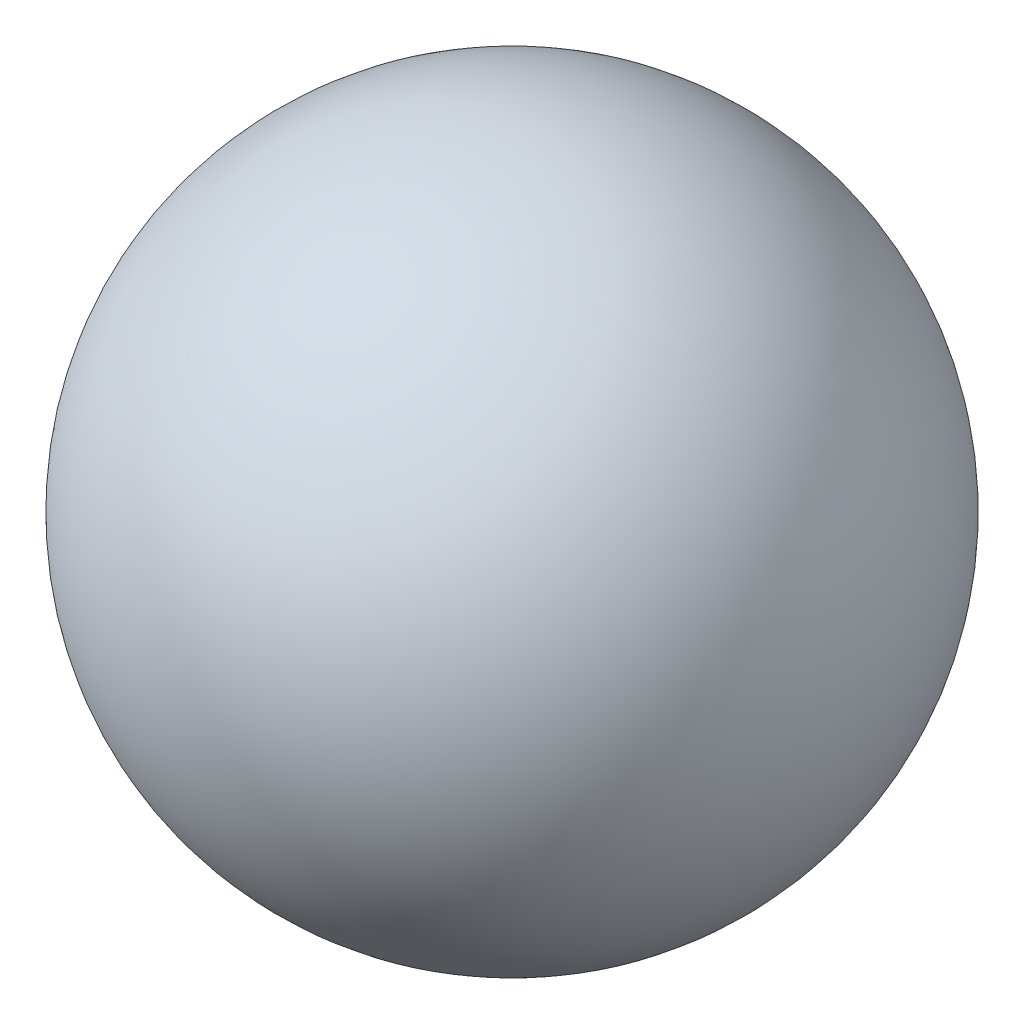
SolidWorks part; units mm, degrees
ref_plane "Front Plane" through (0, 0, 0) normal (0, 0, 1) x (1, 0, 0)
ref_plane "Top Plane" through (0, 0, 0) normal (0, 1, 0) x (1, 0, 0)
ref_plane "Right Plane" through (0, 0, 0) normal (1, 0, 0) x (0, 0, -1)
sketch "Sketch1" plane through (0, 0, 0) normal (0, 0, 1) x (1, 0, 0)
  line L0 (0, 0) -> (0, -50000) construction
  line L1 (0, 36.5) -> (0, -36.5)
  arc A0 (0, -36.5) -> (0, 36.5) centre (0, 0) ccw
  dimension "D1" = 73
revolve "Revolve2" add sketch "Sketch1" angle 360 about L0
